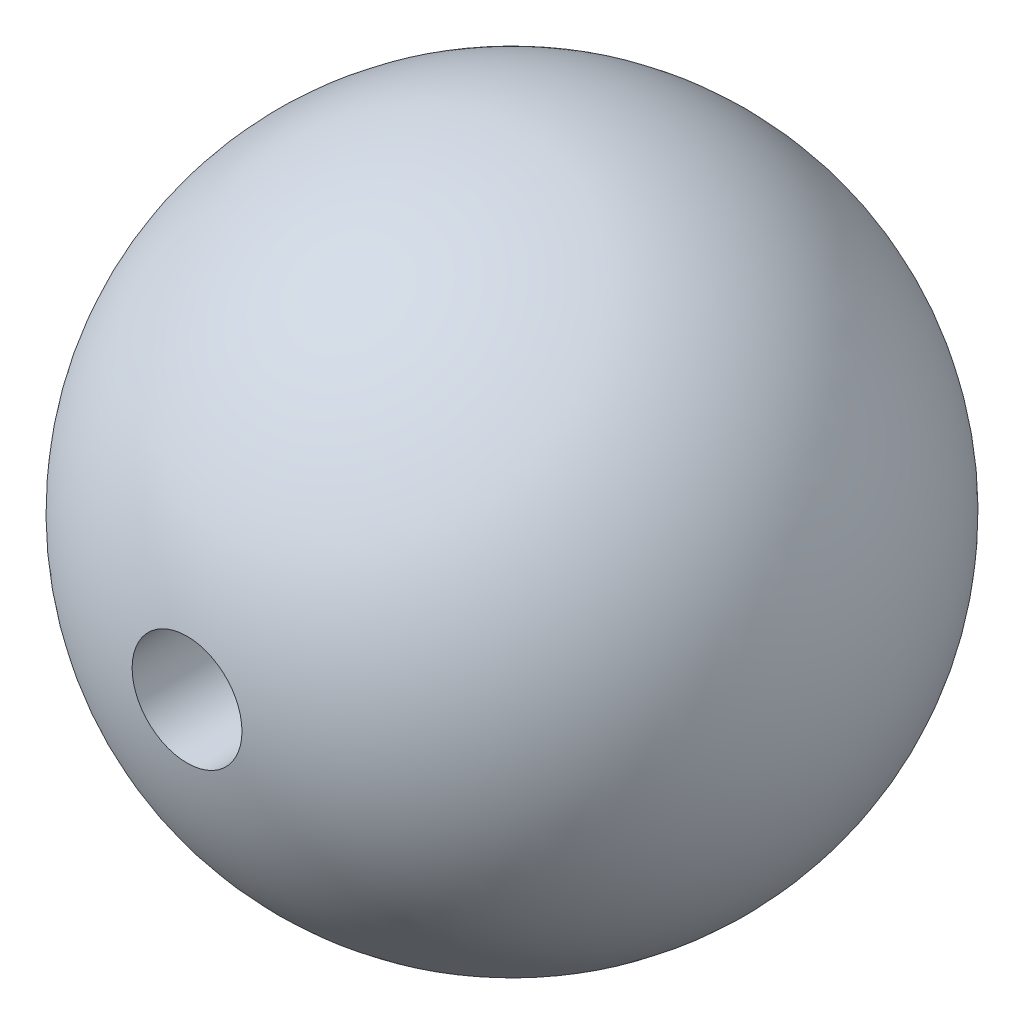
SolidWorks part; units mm, degrees
material "AISI 1020"
ref_plane "Alzado" through (0, 0, 0) normal (0, 0, 1) x (1, 0, 0)
ref_plane "Planta" through (0, 0, 0) normal (0, 1, 0) x (1, 0, 0)
ref_plane "Vista lateral" through (0, 0, 0) normal (1, 0, 0) x (0, 0, -1)
sketch "Croquis1" plane through (0, 0, 0) normal (0, 0, 1) x (1, 0, 0)
  line L0 (0, 55.5761) -> (0, 9.525) construction
  line L1 (0, -9.525) -> (26.9194, -9.525) construction
  line L2 (0, 3.175) -> (0, -58.3038) construction
  line L5 (0, 3.175) -> (3.9624, 3.175)
  line L6 (3.9624, -8.6617) -> (3.9624, 3.175)
  line L7 (0, 3.175) -> (0, 9.525)
  arc A0 (3.9624, -8.6617) -> (0, 9.525) centre (0, 0) ccw
  dimension "D1" = 19.05
  dimension "D2" = 12.7
  dimension "D3" = 3.9624
revolve "Revolución1" add sketch "Croquis1" angle 360 about L7
sketch "Croquis2" plane through (0, 0, 0) normal (0, 0, 1) x (1, 0, 0)
  circle A0 centre (0, 0) radius 1.5875
  dimension "D1" = 3.175
extrude "Cortar-Extruir1" cut sketch "Croquis2" against normal through all both and the other way through all
